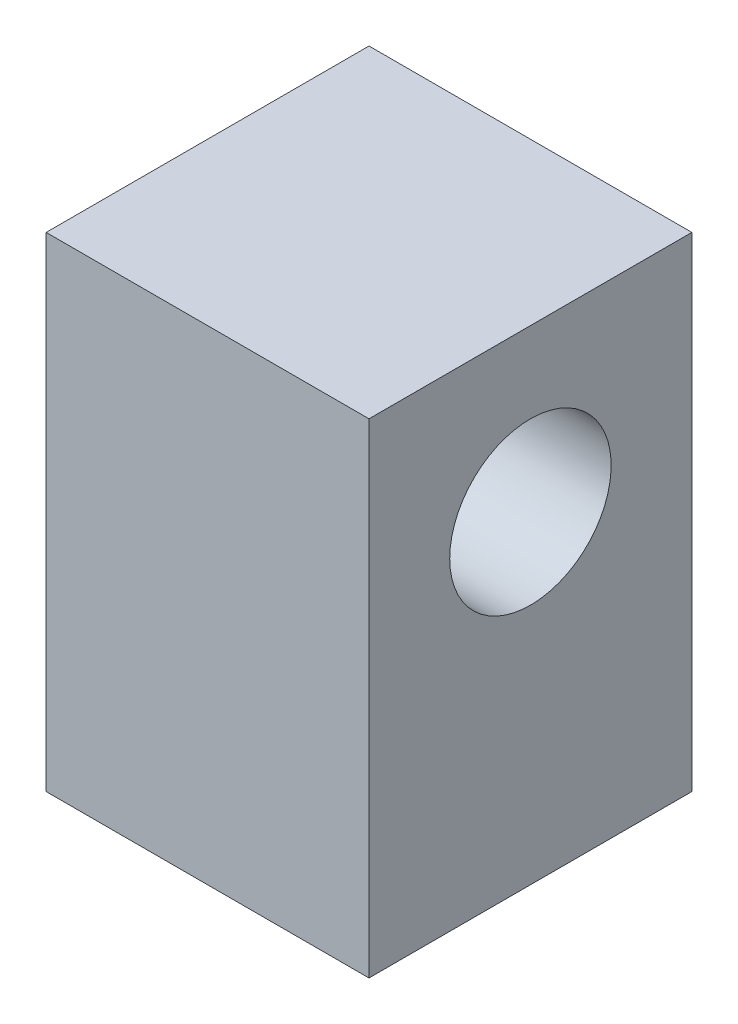
SolidWorks part; units mm, degrees
ref_plane "Front Plane" through (0, 0, 0) normal (0, 0, 1) x (1, 0, 0)
ref_plane "Top Plane" through (0, 0, 0) normal (0, 1, 0) x (1, 0, 0)
ref_plane "Right Plane" through (0, 0, 0) normal (1, 0, 0) x (0, 0, -1)
sketch "Sketch1" plane through (0, 0, 0) normal (0, 1, 0) x (1, 0, 0)
  line L1 (-20, -20) -> (20, -20)
  line L2 (-20, -20) -> (-20, 20)
  line L3 (-20, 20) -> (20, 20)
  line L4 (20, -20) -> (20, 20)
  line L5 (-20, -20) -> (20, 20) construction
  line L6 (-20, 20) -> (20, -20) construction
  point P0 (0, 0)
  dimension "D1" = 40
extrude "Boss-Extrude1" add sketch "Sketch1" along normal blind 60
sketch "Sketch2" plane through (-20, 0, 0) normal (-1, 0, 0) x (0, 0, 1)
  line L0 (-20, 60) -> (20, 60) construction
  circle A0 centre (0, 40) radius 10
  dimension "D1" = 20
  dimension "D2" = 20
extrude "Cut-Extrude1" cut sketch "Sketch2" against normal blind 40
